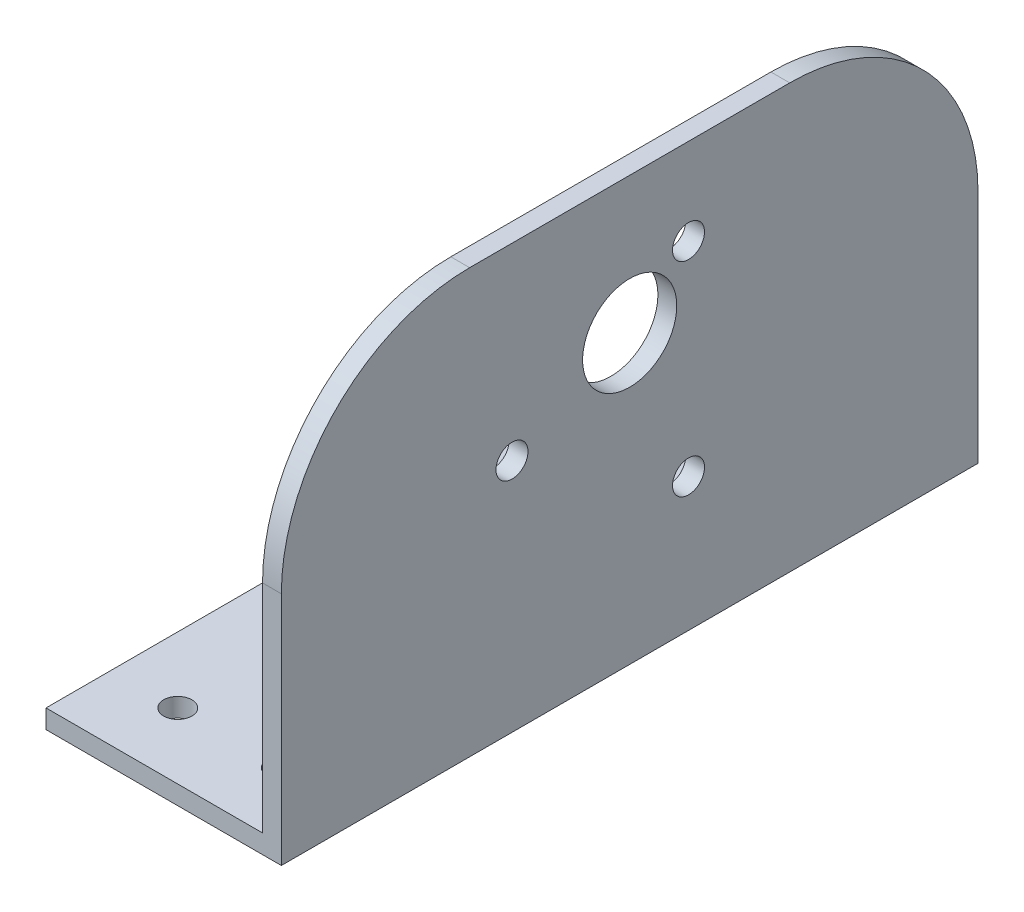
SolidWorks part; units mm, degrees
ref_plane "Piano frontale" through (0, 0, 0) normal (0, 0, 1) x (1, 0, 0)
ref_plane "Piano superiore" through (0, 0, 0) normal (0, 1, 0) x (1, 0, 0)
ref_plane "Piano destro" through (0, 0, 0) normal (1, 0, 0) x (0, 0, -1)
sketch "Sketch4" plane through (0, 0, 0) normal (0, 0, 1) x (1, 0, 0)
  line L0 (0, 0) -> (25, 0)
  line L1 (25, 0) -> (25, 45)
  line L2 (25, 45) -> (23, 45)
  line L3 (23, 45) -> (23, 2)
  line L4 (23, 2) -> (0, 2)
  line L5 (0, 2) -> (0, 0)
extrude "Boss-Extrude3" add sketch "Sketch4" along normal blind 74
sketch "Sketch5" plane through (25, 0, 0) normal (1, 0, 0) x (0, 0, -1)
  line L0 (-37, 0) -> (-37, 30.5)
  line L1 (-74, 0) -> (0, 0) construction
  circle A0 centre (-37, 30.5) radius 5
extrude "Cut-Extrude1" cut sketch "Sketch5" against normal through all
sketch "Sketch6" plane through (25, 0, 0) normal (1, 0, 0) x (0, 0, -1)
  line L0 (-37, 30.5) -> (-37, 25)
  point P4 (-30.75, 14.1747)
  point P8 (-30.75, 35.8253)
  point P10 (-49.5, 25)
hole_wizard "M3 Clearance Hole2" positions "Sketch9" profile "Sketch10" hole size "M3" standard "ANSI Metric" end condition through all
sketch "Sketch9" plane through (25, 0, 0) normal (1, 0, 0) x (0, 0, -1)
  point P0 (-30.75, 14.1747)
  point P3 (-30.75, 35.8253)
  point P6 (-49.5, 25)
sketch "Sketch10" plane through (25, 14.1747, 30.75) normal (0, 1, 0) x (0, 0, -1)
  line L0 (0, 0) -> (0, 25)
  line L1 (0, 25) -> (1.7, 25)
  line L2 (1.7, 25) -> (1.7, 0)
  line L5 (1.7, 0) -> (0, 0)
  line L11 (0, -6.35) -> (0, 107.95) construction
  dimension "Thru Hole Dia." = 3.4
  dimension "Thru Hole Depth" = 25
sketch "Sketch11" plane through (0, 2, 0) normal (0, 1, 0) x (1, 0, 0)
  circle A0 centre (7, -67) radius 1.5
  circle A1 centre (18, -67) radius 1.5
  circle A2 centre (18, -7) radius 1.5
  circle A3 centre (7, -7) radius 1.5
extrude "Cut-Extrude2" cut sketch "Sketch11" against normal through all contours A3 | A2 | A1 | A0
fillet "Fillet1" radius 20 2 edges at (24, 45, 0) (24, 45, 74)
